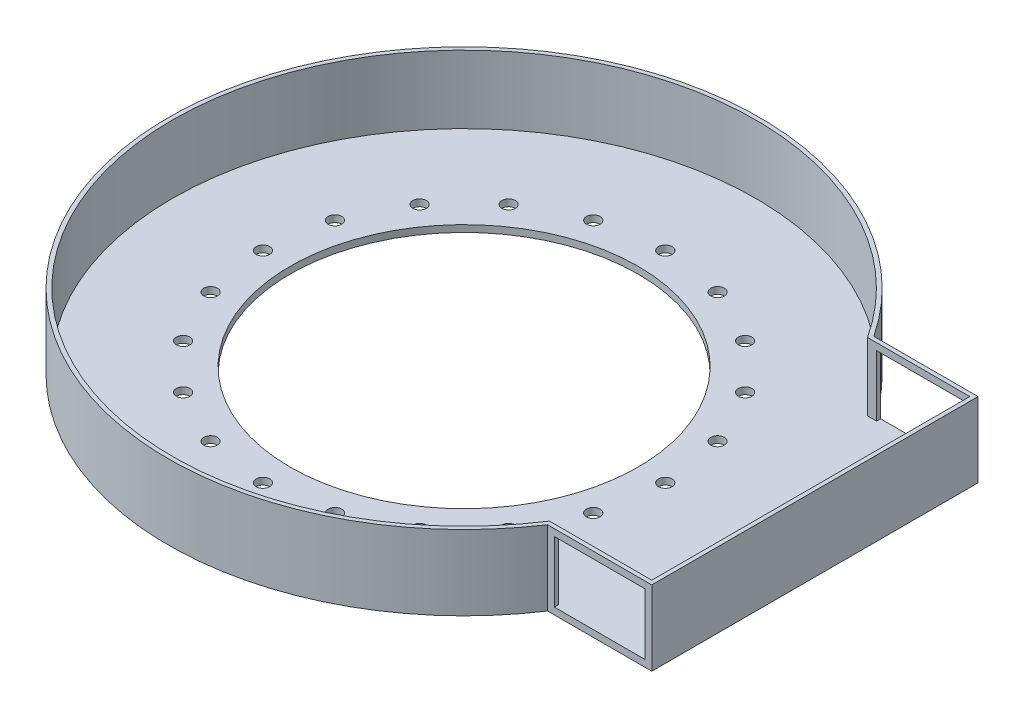
SolidWorks part; units mm, degrees
ref_plane "Plan de face" through (0, 0, 0) normal (0, 0, 1) x (1, 0, 0)
ref_plane "Plan de dessus" through (0, 0, 0) normal (0, 1, 0) x (1, 0, 0)
ref_plane "Plan de droite" through (0, 0, 0) normal (1, 0, 0) x (0, 0, -1)
sketch "Esquisse1" plane through (0, 0, 0) normal (0, 0, 1) x (1, 0, 0)
  line L0 (0, 0) -> (256, 0) construction
  line L1 (0, 0) -> (0, 51.0849) construction
  line L2 (256, 0) -> (336, 0)
  line L3 (256, 0) -> (256, 10)
  line L4 (256, 10) -> (336, 10)
  line L5 (336, 0) -> (336, 10)
  dimension "D1" = 80
  dimension "D2" = 10
  dimension "D3" = 256
revolve "Révolution1" add sketch "Esquisse1" angle 360 about L1
sketch "Esquisse3" plane through (0, 10, 0) normal (0, 1, 0) x (1, 0, 0)
  circle A0 centre (296, 0) radius 10
  dimension "D1" = 20
  dimension "D2" = 296
extrude "Enlèv. mat.-Extru.1" cut sketch "Esquisse3" against normal through all
pattern_circular "Répétition circulaire1" count 20 over 360 about axis through (0, 0, 0) along (0, 1, 0) of "Enlèv. mat.-Extru.1"
sketch "Esquisse4" plane through (0, 0, 0) normal (0, -1, 0) x (1, 0, 0)
  line L0 (0, 0) -> (538.9638, 0) construction
  line L1 (516.151, -240) -> (516.151, 240)
  line L2 (516.151, 240) -> (235.151, 240)
  line L4 (235.151, -240) -> (516.151, -240)
  circle A0 centre (0, 0) radius 336 construction
  arc A1 (235.151, -240) -> (235.151, 240) centre (0, 0) ccw
  point P6 (516.151, 0)
  dimension "D1" = 281
  dimension "D2" = 480
extrude "Boss.-Extru.1" add sketch "Esquisse4" against normal blind 10
sketch "Esquisse5" plane through (0, 0, 0) normal (0, -1, 0) x (1, 0, 0)
  line L0 (235.151, -240) -> (516.151, -240) construction
  line L1 (516.151, 240) -> (235.151, 240) construction
  line L2 (235.151, -240) -> (362.8016, -240)
  line L3 (362.8016, 240) -> (235.151, 240)
  arc A0 (362.8016, 240) -> (362.8016, -240) centre (0, 0) ccw
  arc A1 (235.151, 240) -> (235.151, -240) centre (0, 0) ccw construction
  arc A2 (235.151, 240) -> (235.151, -240) centre (0, 0) ccw
  dimension "D1" = 435
extrude "Boss.-Extru.2" add sketch "Esquisse5" against normal blind 10
sketch "Esquisse6" plane through (0, 10, 0) normal (0, 1, 0) x (1, 0, 0)
  line L6 (359.5622, -234) -> (510.151, -234)
  line L7 (510.151, -234) -> (510.151, 234)
  line L8 (510.151, 234) -> (359.5622, 234)
  line L9 (359.5622, -234) -> (510.151, -234)
  line L10 (510.151, -234) -> (510.151, 234)
  line L11 (510.151, 234) -> (359.5622, 234)
  arc A2 (359.5622, 234) -> (359.5622, -234) centre (0, 0) ccw
  arc A3 (359.5622, 234) -> (359.5622, -234) centre (0, 0) ccw
  arc M5 (362.8016, 240) -> (362.8016, -240) centre (0, 0) ccw
  line M6 (362.8016, -240) -> (516.151, -240)
  line M7 (516.151, -240) -> (516.151, 240)
  line M8 (516.151, 240) -> (362.8016, 240)
  dimension "D1" = 6
extrude "Boss.-Extru.3" add sketch "Esquisse6" along normal blind 100 contours A3 L11 L10 L9 M8 M5 M6 M7
sketch "Esquisse8" plane through (0, 0, 240) normal (0, 0, 1) x (1, 0, 0)
  line L8 (372.8016, 100) -> (372.8016, 10)
  line L9 (372.8016, 10) -> (506.151, 10)
  line L10 (506.151, 10) -> (506.151, 100)
  line L11 (506.151, 100) -> (372.8016, 100)
  line L12 (372.8016, 100) -> (372.8016, 10)
  line L13 (372.8016, 10) -> (506.151, 10)
  line L14 (506.151, 10) -> (506.151, 100)
  line L15 (506.151, 100) -> (372.8016, 100)
  dimension "D1" = 10
extrude "Enlèv. mat.-Extru.2" cut sketch "Esquisse8" against normal through all
